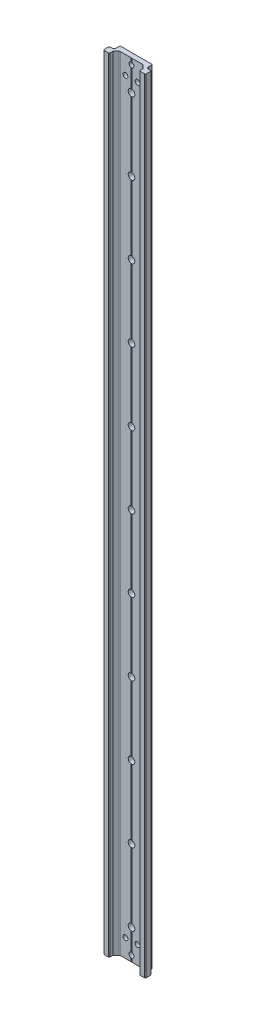
SolidWorks part; units mm, degrees
ref_plane "Plan de face" through (0, 0, 0) normal (0, 0, 1) x (1, 0, 0)
ref_plane "Plan de dessus" through (0, 0, 0) normal (0, 1, 0) x (1, 0, 0)
ref_plane "Plan de droite" through (0, 0, 0) normal (1, 0, 0) x (0, 0, -1)
ref_plane "Plan1" through (0, 325, 0) normal (0, 1, 0) x (1, 0, 0)
sketch "Esquisse1" plane through (0, 325, 0) normal (0, 1, 0) x (1, 0, 0)
  line L0 (-9.7, 1) -> (9.7, 1)
  line L1 (9.7, 1) -> (12.5, -1.8)
  line L2 (12.5, -1.8) -> (12.5, -5)
  line L3 (12.5, -5) -> (17.5, -5)
  line L4 (17.5, -5) -> (17.5, 5)
  line L5 (17.5, 5) -> (-17.5, 5)
  line L6 (-17.5, 5) -> (-17.5, -5)
  line L7 (-17.5, -5) -> (-12.5, -5)
  line L8 (-12.5, -5) -> (-12.5, -1.8)
  line L9 (-12.5, -1.8) -> (-9.7, 1)
extrude "Boss.-Extru.1" add sketch "Esquisse1" against normal blind 650
sketch "Esquisse2" plane through (0, -325, 0) normal (0, -1, 0) x (1, 0, 0)
  line L0 (-14.3, 0) -> (-17.5, 0)
  line L1 (-17.5, 0) -> (-17.5, -5)
  line L2 (-17.5, -5) -> (-13.5, -5)
  line L3 (-13.5, -5) -> (-13.5, -0.8)
  line L4 (-13.5, -0.8) -> (-14.3, 0)
extrude "Enlèv. mat.-Extru.1" cut sketch "Esquisse2" against normal through all
sketch "Esquisse3" plane through (0, -325, 0) normal (0, -1, 0) x (1, 0, 0)
  line L0 (0.25, -1) -> (-0.25, -1)
  line L1 (-0.25, -1) -> (0, -1.1443)
  line L2 (0, -1.1443) -> (0.25, -1)
extrude "Enlèv. mat.-Extru.2" cut sketch "Esquisse3" against normal blind 650
sketch "Esquisse4" plane through (0, -325, 0) normal (0, -1, 0) x (1, 0, 0)
  line L0 (13.5, -0.8) -> (13.5, -5)
  line L1 (13.5, -5) -> (17.5, -5)
  line L2 (17.5, -5) -> (17.5, 0)
  line L3 (17.5, 0) -> (14.3, 0)
  line L4 (14.3, 0) -> (13.5, -0.8)
extrude "Enlèv. mat.-Extru.3" cut sketch "Esquisse4" against normal through all
sketch "Esquisse5" plane through (0, -325, 0) normal (0, -1, 0) x (1, 0, 0)
  line L0 (-7.5, -5) -> (7.5, -5)
  line L1 (7.5, -5) -> (7.4, -4.9)
  line L2 (7.4, -4.9) -> (-7.4, -4.9)
  line L3 (-7.4, -4.9) -> (-7.5, -5)
extrude "Enlèv. mat.-Extru.4" cut sketch "Esquisse5" against normal blind 650
hole_wizard "Diamètre du perçage Ø5.5 (5.5)1" positions "Esquisse7" profile "Esquisse6" hole size "Ø5.5" standard "Ansi Metric"
sketch "Esquisse7" plane through (0, 0, -4.9) normal (0, 0, -1) x (-1, 0, 0)
  point P0 (0, 300)
  point P1 (0, 240)
  point P2 (0, 180)
  point P3 (0, 120)
  point P4 (0, 60)
  point P5 (0, 0)
  point P6 (0, -60)
  point P7 (0, -120)
  point P8 (0, -180)
  point P9 (0, -240)
  point P10 (0, -300)
sketch "Esquisse6" plane through (0, 300, -4.9) normal (1, 0, 0) x (0, 1, 0)
  line L0 (0, 0) -> (0, 9.9)
  line L1 (0, 9.9) -> (2.75, 9.9)
  line L2 (2.75, 9.9) -> (2.75, 0)
  line L5 (2.75, 0) -> (0, 0)
  line L11 (0, -6.35) -> (0, 107.95) construction
  dimension "Diamètre du perçage jusqu'au prochain" = 5.5
  dimension "Profondeur du perçage jusqu'au prochain" = 9.9
chamfer "Chanfrein1" distance 0.5 angle 45 2 edges at (17.5, 0, 5) (-17.5, 0, 5)
chamfer "Chanfrein2" distance 0.3 angle 45 2 edges at (-13.5, 0, -5) (13.5, 0, -5)
chamfer "Chanfrein3" distance 0.5 angle 45 3 edges at (12.5, 0, 5) (-17.5, 0, 0) (-12.5, 0, 5)
chamfer "Chanfrein4" distance 0.5 angle 45 1 edges at (17.5, 0, 0)
fillet "Congé1" radius 1.5 2 edges at (9.7, 0, -1) (-9.7, 0, -1)
fillet "Congé2" radius 2 2 edges at (13.5, 0, -0.8) (-13.5, 0, -0.8)
sketch "Esquisse8" plane through (0, 0, -1) normal (0, 0, 1) x (1, 0, 0)
  line L0 (-9.0787, -325) -> (-0.25, -325) construction
  line L1 (0.25, -325) -> (9.0787, -325) construction
  line L2 (-9.0787, 325) -> (-0.25, 325) construction
  line L3 (0.25, 325) -> (9.0787, 325) construction
  line L4 (0, 325) -> (0, 302.75) construction
  circle A0 centre (-5, -310) radius 2
  circle A1 centre (5, -310) radius 2
  circle A2 centre (-5, 310) radius 2
  circle A3 centre (5, 310) radius 2
  circle A4 centre (0, -320) radius 2.0932
  circle A5 centre (0, 320) radius 2
  dimension "D1" = 4
  dimension "D2" = 4
  dimension "D3" = 4
  dimension "D4" = 4
  dimension "D13" = 4.1865
  dimension "D15" = 4
  dimension "D5" = 15
  dimension "D6" = 15
  dimension "D7" = 15
  dimension "D8" = 15
  dimension "D9" = 5
  dimension "D10" = 5
  dimension "D11" = 5
  dimension "D12" = 5
  dimension "D14" = 5
  dimension "D16" = 5
extrude "Enlèv. mat.-Extru.5" cut sketch "Esquisse8" against normal blind 10
